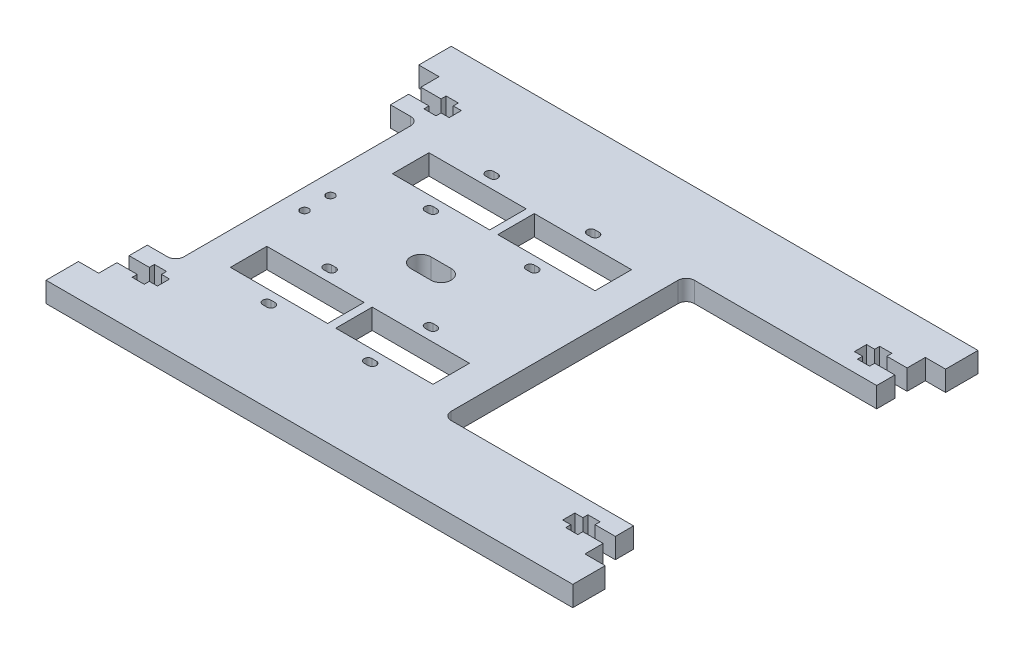
SolidWorks part; units mm, degrees
material "Maple"
ref_plane "Front Plane" through (0, 0, 0) normal (0, 0, 1) x (1, 0, 0)
ref_plane "Top Plane" through (0, 0, 0) normal (0, 1, 0) x (1, 0, 0)
ref_plane "Right Plane" through (0, 0, 0) normal (1, 0, 0) x (0, 0, -1)
sketch "Sketch1" plane through (0, 0, 0) normal (0, 1, 0) x (1, 0, 0)
  line L0 (27, 77.5) -> (28, 77.5) construction
  line L1 (0, 0) -> (120, 0)
  line L2 (0, 0) -> (0, 100)
  line L3 (0, 100) -> (120, 100)
  line L4 (120, 0) -> (120, 100)
  line L5 (27, 78.5) -> (28, 78.5)
  line L6 (27, 76.5) -> (28, 76.5)
  line L7 (15, 70) -> (65, 70) construction
  line L8 (40, 70) -> (40, 74.5) construction
  line L9 (15, 74.5) -> (65, 74.5)
  line L10 (15, 74.5) -> (15, 65.5)
  line L11 (15, 65.5) -> (65, 65.5)
  line L12 (65, 74.5) -> (65, 65.5)
  line L13 (8.0992, 50) -> (69.3023, 50) construction
  line L14 (40, 74.5) -> (15, 65.5) construction
  line L15 (27.5, 77.5) -> (27.5, 70) construction
  line L16 (40, 74.5) -> (40, 90) construction
  line L17 (53, 77.5) -> (52, 77.5) construction
  line L18 (53, 78.5) -> (52, 78.5)
  line L19 (53, 76.5) -> (52, 76.5)
  line L20 (27, 62.5) -> (28, 62.5) construction
  line L21 (27, 61.5) -> (28, 61.5)
  line L22 (27, 63.5) -> (28, 63.5)
  line L23 (53, 62.5) -> (52, 62.5) construction
  line L24 (53, 61.5) -> (52, 61.5)
  line L25 (53, 63.5) -> (52, 63.5)
  line L26 (27, 22.5) -> (28, 22.5) construction
  line L27 (27, 21.5) -> (28, 21.5)
  line L28 (27, 23.5) -> (28, 23.5)
  line L29 (53, 22.5) -> (52, 22.5) construction
  line L30 (53, 21.5) -> (52, 21.5)
  line L31 (53, 23.5) -> (52, 23.5)
  line L32 (27, 37.5) -> (28, 37.5) construction
  line L33 (27, 38.5) -> (28, 38.5)
  line L34 (27, 36.5) -> (28, 36.5)
  line L35 (53, 37.5) -> (52, 37.5) construction
  line L36 (53, 38.5) -> (52, 38.5)
  line L37 (53, 36.5) -> (52, 36.5)
  line L38 (27.5, 22.5) -> (27.5, 30) construction
  line L39 (40, 25.5) -> (15, 34.5) construction
  line L40 (40, 30) -> (40, 25.5) construction
  line L41 (15, 30) -> (65, 30) construction
  line L42 (65, 25.5) -> (65, 34.5)
  line L43 (15, 34.5) -> (65, 34.5)
  line L44 (15, 25.5) -> (15, 34.5)
  line L45 (15, 25.5) -> (65, 25.5)
  arc A0 (27, 78.5) -> (27, 76.5) centre (27, 77.5) ccw
  arc A1 (28, 76.5) -> (28, 78.5) centre (28, 77.5) ccw
  arc A2 (53, 78.5) -> (53, 76.5) centre (53, 77.5) cw
  arc A3 (52, 76.5) -> (52, 78.5) centre (52, 77.5) cw
  arc A4 (27, 61.5) -> (27, 63.5) centre (27, 62.5) cw
  arc A5 (28, 63.5) -> (28, 61.5) centre (28, 62.5) cw
  arc A6 (53, 61.5) -> (53, 63.5) centre (53, 62.5) ccw
  arc A7 (52, 63.5) -> (52, 61.5) centre (52, 62.5) ccw
  arc A8 (27, 21.5) -> (27, 23.5) centre (27, 22.5) cw
  arc A9 (28, 23.5) -> (28, 21.5) centre (28, 22.5) cw
  arc A10 (53, 21.5) -> (53, 23.5) centre (53, 22.5) ccw
  arc A11 (52, 23.5) -> (52, 21.5) centre (52, 22.5) ccw
  arc A12 (27, 38.5) -> (27, 36.5) centre (27, 37.5) ccw
  arc A13 (28, 36.5) -> (28, 38.5) centre (28, 37.5) ccw
  arc A14 (53, 38.5) -> (53, 36.5) centre (53, 37.5) cw
  arc A15 (52, 36.5) -> (52, 38.5) centre (52, 37.5) cw
  point P7 (27.5, 77.5)
  point P20 (26, 77.5)
  point P21 (29, 77.5)
  point P29 (52.5, 77.5)
  point P36 (27.5, 62.5)
  point P43 (52.5, 62.5)
  point P50 (27.5, 22.5)
  point P57 (52.5, 22.5)
  point P64 (27.5, 37.5)
  point P71 (52.5, 37.5)
  dimension "D1" = 120
  dimension "D2" = 50
  dimension "D3" = 2
  dimension "D4" = 2
  dimension "D5" = 3
  dimension "D6" = 9
  dimension "D7" = 40
  dimension "D8" = 50
  dimension "D9" = 50
  dimension "D10" = 40
extrude "Boss-Extrude1" add sketch "Sketch1" along normal blind 5
sketch "Sketch2" plane through (0, 5, 0) normal (0, 1, 0) x (1, 0, 0)
  line L0 (60, 100) -> (60, 73.3658) construction
  line L1 (120, 100) -> (125, 100)
  line L2 (120, 100) -> (120, 92)
  line L3 (120, 92) -> (125, 92)
  line L4 (125, 100) -> (125, 92)
  line L5 (120, 0) -> (125, 0)
  line L6 (120, 0) -> (120, 8)
  line L7 (120, 8) -> (125, 8)
  line L8 (125, 0) -> (125, 8)
  line L9 (120, 100) -> (0, 100) construction
  line L10 (-5, 0) -> (-5, 8)
  line L11 (0, 8) -> (-5, 8)
  line L12 (0, 0) -> (0, 8)
  line L13 (0, 0) -> (-5, 0)
  line L14 (-5, 100) -> (-5, 92)
  line L15 (0, 92) -> (-5, 92)
  line L16 (0, 100) -> (0, 92)
  line L17 (0, 100) -> (-5, 100)
  dimension "D1" = 5
  dimension "D2" = 8
extrude "Boss-Extrude2" add sketch "Sketch2" against normal up to surface (5 mm away) up to face at (60, 0, -50)
sketch "Sketch3" plane through (0, 5, 0) normal (0, 1, 0) x (1, 0, 0)
  line L0 (120, 8) -> (120, 92) construction
  line L1 (120, 80) -> (73, 80)
  line L2 (120, 80) -> (120, 20)
  line L3 (120, 20) -> (73, 20)
  line L4 (73, 80) -> (73, 20)
  line L5 (0, 92) -> (0, 8) construction
  line L6 (65, 65.5) -> (65, 74.5) construction
  line L7 (125, 100) -> (-5, 100) construction
  line L8 (-5, 0) -> (125, 0) construction
  line L9 (0, 80) -> (7, 80)
  line L10 (0, 80) -> (0, 20)
  line L11 (0, 20) -> (7, 20)
  line L12 (7, 80) -> (7, 20)
  line L13 (15, 74.5) -> (15, 65.5) construction
  point P20 (15, 70)
  dimension "D1" = 8
  dimension "D2" = 20
  dimension "D3" = 20
  dimension "D4" = 8
extrude "Cut-Extrude1" cut sketch "Sketch3" against normal through all
fillet "Fillet1" radius 2 4 edges at (73, 2.5, -20) (73, 2.5, -80) (7, 2.5, -20) (7, 2.5, -80)
sketch "Sketch4" plane through (0, 5, 0) normal (0, 1, 0) x (1, 0, 0)
  line L0 (7, 22) -> (7, 78) construction
  line L1 (15, 65.5) -> (15, 34.5) construction
  line L2 (12, 53.2) -> (12, 46.8) construction
  line L3 (12, 50) -> (15, 50) construction
  line L4 (37.5, 50) -> (42.5, 50) construction
  line L5 (37.5, 52.5) -> (42.5, 52.5)
  line L6 (37.5, 47.5) -> (42.5, 47.5)
  line L7 (40, 65.5) -> (40, 34.5) construction
  line L8 (15, 65.5) -> (65, 65.5) construction
  line L9 (65, 34.5) -> (15, 34.5) construction
  circle A0 centre (12, 53.2) radius 1
  circle A1 centre (12, 46.8) radius 1
  arc A2 (37.5, 52.5) -> (37.5, 47.5) centre (37.5, 50) ccw
  arc A3 (42.5, 47.5) -> (42.5, 52.5) centre (42.5, 50) ccw
  point P14 (40, 50)
  dimension "D1" = 2
  dimension "D2" = 6.4
  dimension "D3" = 5
  dimension "D4" = 5
  dimension "D5" = 5
extrude "Cut-Extrude2" cut sketch "Sketch4" against normal through all
sketch "Sketch5" plane through (0, 5, 0) normal (0, 1, 0) x (1, 0, 0)
  line L0 (120, 15.5) -> (115, 15.5)
  line L1 (120, 8) -> (120, 20) construction
  line L2 (115, 15.5) -> (115, 16.75)
  line L3 (115, 16.75) -> (112, 16.75)
  line L4 (112, 16.75) -> (112, 15.5)
  line L5 (112, 15.5) -> (110, 15.5)
  line L6 (110, 15.5) -> (110, 12.5)
  line L7 (110, 12.5) -> (112, 12.5)
  line L8 (112, 12.5) -> (112, 11.25)
  line L9 (112, 11.25) -> (115, 11.25)
  line L10 (115, 11.25) -> (115, 12.5)
  line L11 (115, 12.5) -> (120, 12.5)
  line L12 (120, 12.5) -> (120, 15.5)
  line L13 (60, 0) -> (60, 100) construction
  line L14 (-5, 0) -> (125, 0) construction
  line L15 (125, 100) -> (-5, 100) construction
  line L16 (73, 50) -> (7, 50) construction
  line L17 (73, 78) -> (73, 22) construction
  line L18 (7, 22) -> (7, 78) construction
  line L19 (0, 12.5) -> (0, 15.5)
  line L20 (5, 12.5) -> (0, 12.5)
  line L21 (5, 11.25) -> (5, 12.5)
  line L22 (8, 11.25) -> (5, 11.25)
  line L23 (8, 12.5) -> (8, 11.25)
  line L24 (10, 12.5) -> (8, 12.5)
  line L25 (10, 15.5) -> (10, 12.5)
  line L26 (8, 15.5) -> (10, 15.5)
  line L27 (8, 16.75) -> (8, 15.5)
  line L28 (5, 16.75) -> (8, 16.75)
  line L29 (5, 15.5) -> (5, 16.75)
  line L30 (0, 15.5) -> (5, 15.5)
  line L31 (0, 84.5) -> (5, 84.5)
  line L32 (5, 84.5) -> (5, 83.25)
  line L33 (5, 83.25) -> (8, 83.25)
  line L34 (8, 83.25) -> (8, 84.5)
  line L35 (8, 84.5) -> (10, 84.5)
  line L36 (10, 84.5) -> (10, 87.5)
  line L37 (10, 87.5) -> (8, 87.5)
  line L38 (8, 87.5) -> (8, 88.75)
  line L39 (8, 88.75) -> (5, 88.75)
  line L40 (5, 88.75) -> (5, 87.5)
  line L41 (5, 87.5) -> (0, 87.5)
  line L42 (0, 87.5) -> (0, 84.5)
  line L43 (120, 87.5) -> (120, 84.5)
  line L44 (115, 87.5) -> (120, 87.5)
  line L45 (115, 88.75) -> (115, 87.5)
  line L46 (112, 88.75) -> (115, 88.75)
  line L47 (112, 87.5) -> (112, 88.75)
  line L48 (110, 87.5) -> (112, 87.5)
  line L49 (110, 84.5) -> (110, 87.5)
  line L50 (112, 84.5) -> (110, 84.5)
  line L51 (112, 83.25) -> (112, 84.5)
  line L52 (115, 83.25) -> (112, 83.25)
  line L53 (115, 84.5) -> (115, 83.25)
  line L54 (120, 84.5) -> (115, 84.5)
  point P4 (120, 14)
  point P15 (117.5, 12.5)
  dimension "D1" = 3
  dimension "D2" = 3
  dimension "D3" = 2
  dimension "D4" = 5
  dimension "D5" = 5.5
extrude "Cut-Extrude3" cut sketch "Sketch5" against normal through all
sketch "Sketch6" plane through (0, 5, 0) normal (0, 1, 0) x (1, 0, 0)
  line L1 (65, 74.5) -> (15, 74.5) construction
  line L2 (39, 74.5) -> (41, 74.5)
  line L3 (39, 74.5) -> (39, 65.5)
  line L4 (39, 65.5) -> (41, 65.5)
  line L6 (41, 74.5) -> (41, 65.5)
  line L7 (15, 65.5) -> (65, 65.5) construction
  line L8 (65, 34.5) -> (15, 34.5) construction
  line L9 (39, 34.5) -> (41, 34.5)
  line L10 (39, 34.5) -> (39, 25.5)
  line L11 (39, 25.5) -> (41, 25.5)
  line L12 (41, 34.5) -> (41, 25.5)
  line L13 (15, 25.5) -> (65, 25.5) construction
  point P8 (40, 74.5)
  dimension "D1" = 2
extrude "Boss-Extrude3" add sketch "Sketch6" against normal up to surface (5 mm away) up to face at (57.7778, 0, -50)
